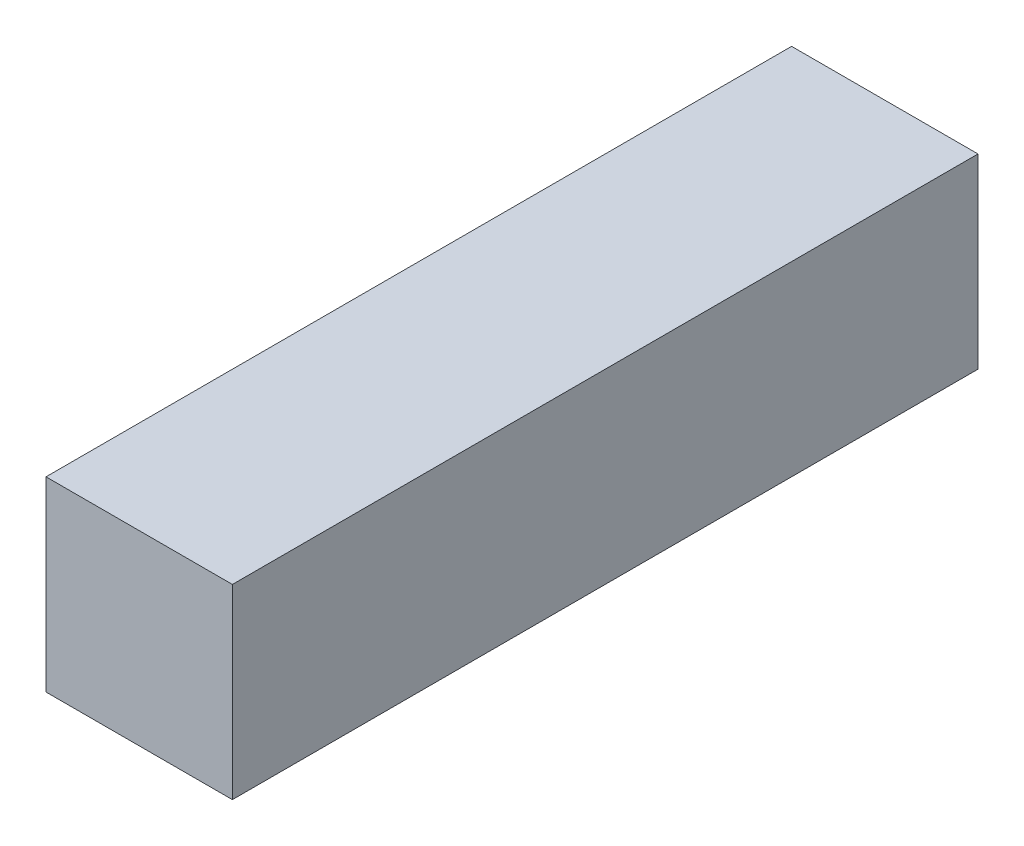
SolidWorks part; units mm, degrees
material "AISI 1045 Steel, cold drawn"
ref_plane "Front Plane" through (0, 0, 0) normal (0, 0, 1) x (1, 0, 0)
ref_plane "Top Plane" through (0, 0, 0) normal (0, 1, 0) x (1, 0, 0)
ref_plane "Right Plane" through (0, 0, 0) normal (1, 0, 0) x (0, 0, -1)
sketch "Sketch1" plane through (0, 0, 0) normal (0, 0, 1) x (1, 0, 0)
  line L1 (-3.175, -3.175) -> (3.175, -3.175)
  line L2 (-3.175, -3.175) -> (-3.175, 3.175)
  line L3 (-3.175, 3.175) -> (3.175, 3.175)
  line L4 (3.175, -3.175) -> (3.175, 3.175)
  line L5 (-3.175, -3.175) -> (3.175, 3.175) construction
  line L6 (-3.175, 3.175) -> (3.175, -3.175) construction
  point P0 (0, 0)
  dimension "D1" = 6.35
  dimension "D2" = 6.35
extrude "Boss-Extrude1" add sketch "Sketch1" along normal blind 25.4
